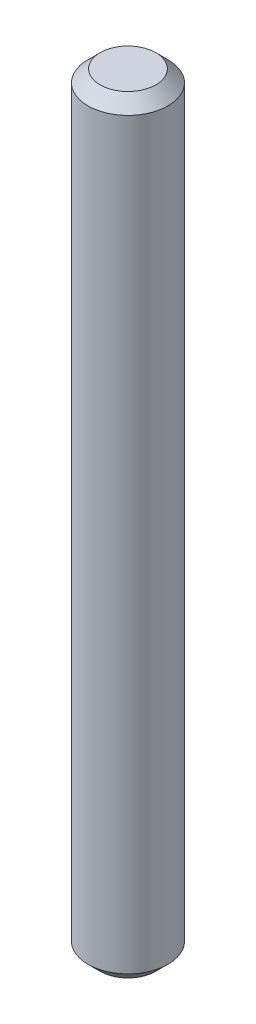
SolidWorks part; units mm, degrees
ref_plane "Front Plane" through (0, 0, 0) normal (0, 0, 1) x (1, 0, 0)
ref_plane "Top Plane" through (0, 0, 0) normal (0, 1, 0) x (1, 0, 0)
ref_plane "Right Plane" through (0, 0, 0) normal (1, 0, 0) x (0, 0, -1)
sketch "Sketch1" plane through (0, 0, 0) normal (0, 1, 0) x (1, 0, 0)
  circle A0 centre (0, 0) radius 9.9
  dimension "D1" = 19.8
extrude "Boss-Extrude1" add sketch "Sketch1" along normal blind 190
chamfer "Chamfer1" distance 3 angle 45 2 edges at (0, 0, 9.9) (0, 190, 9.9)
